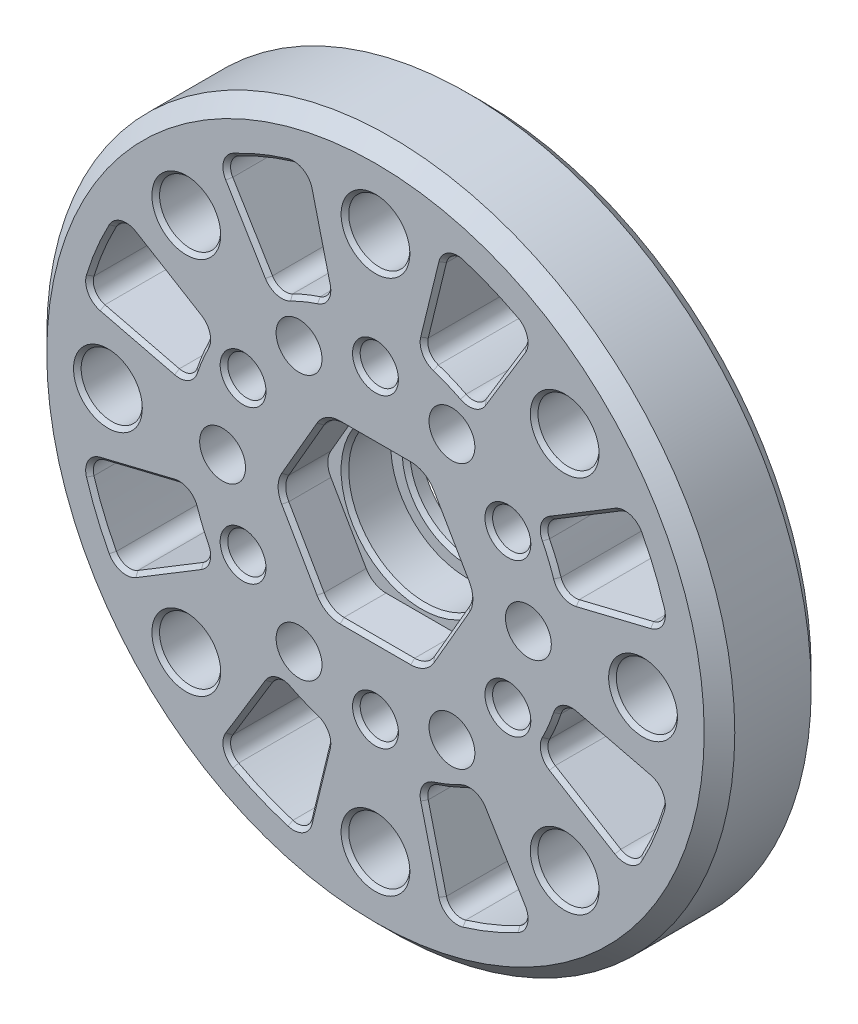
SolidWorks part; units mm, degrees
material "A2017"
ref_plane "正面" through (0, 0, 0) normal (0, 0, 1) x (1, 0, 0)
ref_plane "平面" through (0, 0, 0) normal (0, 1, 0) x (1, 0, 0)
ref_plane "右側面" through (0, 0, 0) normal (1, 0, 0) x (0, 0, -1)
sketch "ｽｹｯﾁ1" plane through (0, 0, 0) normal (0, 0, 1) x (1, 0, 0)
  circle A0 centre (0, 0) radius 17.5 construction
  circle A1 centre (0, 17.5) radius 2
  circle A2 centre (12.3744, 12.3744) radius 2
  circle A3 centre (17.5, 0) radius 2
  circle A4 centre (12.3744, -12.3744) radius 2
  circle A5 centre (0, -17.5) radius 2
  circle A6 centre (-12.3744, -12.3744) radius 2
  circle A7 centre (-17.5, 0) radius 2
  circle A8 centre (-12.3744, 12.3744) radius 2
  circle A9 centre (0, 0) radius 22.5
  point P21 (0, 0)
  dimension "D1" = 35
  dimension "D2" = 4
  dimension "D4" = 45
  dimension "D3" = 8
extrude "ﾎﾞｽ - 押し出し1" add sketch "ｽｹｯﾁ1" along normal blind 7
sketch "ｽｹｯﾁ2" plane through (0, 0, 7) normal (0, 0, 1) x (1, 0, 0)
  circle A0 centre (0, 7.1696) radius 1.0285
extrude "ﾎﾞｽ - 押し出し2" [suppressed] add sketch "ｽｹｯﾁ2" along normal blind 10
sketch "ｽｹｯﾁ3" plane through (0, 0, 7) normal (0, 0, 1) x (1, 0, 0)
  circle A0 centre (2, 0) radius 3
  dimension "D1" = 6
  dimension "D2" = 2
extrude "ｶｯﾄ - 押し出し1" [suppressed] cut sketch "ｽｹｯﾁ3" against normal through all
sketch "ｽｹｯﾁ5" plane through (0, 0, 7) normal (0, 0, 1) x (1, 0, 0)
  line L0 (0, 0) -> (0, 22) construction
  line L1 (0, 0) -> (7.5244, 20.6732) construction
  arc A1 (-7.5244, 20.6732) -> (7.5244, 20.6732) centre (0, 0) cw construction
  arc A2 (7.952, 21.8479) -> (-7.952, 21.8479) centre (0, 0) ccw
  arc A3 (7.0969, 19.4986) -> (-7.0969, 19.4986) centre (0, 0) ccw
  arc A4 (7.0969, 19.4986) -> (7.952, 21.8479) centre (7.5244, 20.6732) ccw
  arc A5 (-7.952, 21.8479) -> (-7.0969, 19.4986) centre (-7.5244, 20.6732) ccw
  arc A6 (14.1413, 16.853) -> (21.6658, 3.8203) centre (0, 0) cw construction
  arc A7 (22.8968, 4.0373) -> (14.9448, 17.8105) centre (0, 0) ccw
  arc A8 (20.4348, 3.6032) -> (13.3378, 15.8954) centre (0, 0) ccw
  arc A9 (20.4348, 3.6032) -> (22.8968, 4.0373) centre (21.6658, 3.8203) ccw
  arc A10 (14.9448, 17.8105) -> (13.3378, 15.8954) centre (14.1413, 16.853) ccw
  arc A11 (21.6658, -3.8203) -> (14.1413, -16.853) centre (0, 0) cw construction
  arc A12 (14.9448, -17.8105) -> (22.8968, -4.0373) centre (0, 0) ccw
  arc A13 (13.3378, -15.8954) -> (20.4348, -3.6032) centre (0, 0) ccw
  arc A14 (13.3378, -15.8954) -> (14.9448, -17.8105) centre (14.1413, -16.853) ccw
  arc A15 (22.8968, -4.0373) -> (20.4348, -3.6032) centre (21.6658, -3.8203) ccw
  arc A16 (7.5244, -20.6732) -> (-7.5244, -20.6732) centre (0, 0) cw construction
  arc A17 (-7.952, -21.8479) -> (7.952, -21.8479) centre (0, 0) ccw
  arc A18 (-7.0969, -19.4986) -> (7.0969, -19.4986) centre (0, 0) ccw
  arc A19 (-7.0969, -19.4986) -> (-7.952, -21.8479) centre (-7.5244, -20.6732) ccw
  arc A20 (7.952, -21.8479) -> (7.0969, -19.4986) centre (7.5244, -20.6732) ccw
  arc A21 (-14.1413, -16.853) -> (-21.6658, -3.8203) centre (0, 0) cw construction
  arc A22 (-22.8968, -4.0373) -> (-14.9448, -17.8105) centre (0, 0) ccw
  arc A23 (-20.4348, -3.6032) -> (-13.3378, -15.8954) centre (0, 0) ccw
  arc A24 (-20.4348, -3.6032) -> (-22.8968, -4.0373) centre (-21.6658, -3.8203) ccw
  arc A25 (-14.9448, -17.8105) -> (-13.3378, -15.8954) centre (-14.1413, -16.853) ccw
  arc A26 (-21.6658, 3.8203) -> (-14.1413, 16.853) centre (0, 0) cw construction
  arc A27 (-14.9448, 17.8105) -> (-22.8968, 4.0373) centre (0, 0) ccw
  arc A28 (-13.3378, 15.8954) -> (-20.4348, 3.6032) centre (0, 0) ccw
  arc A29 (-13.3378, 15.8954) -> (-14.9448, 17.8105) centre (-14.1413, 16.853) ccw
  arc A30 (-22.8968, 4.0373) -> (-20.4348, 3.6032) centre (-21.6658, 3.8203) ccw
  circle A31 centre (0, 0) radius 22 construction
  point P7 (0, 22)
  point P19 (19.0526, 11)
  point P26 (19.0526, -11)
  point P33 (0, -22)
  point P40 (-19.0526, -11)
  point P47 (-19.0526, 11)
  point P52 (0, 0)
  dimension "D1" = 1.25
  dimension "D3" = 20
  dimension "D2" = 44
  dimension "D4" = 6
extrude "ｶｯﾄ - 押し出し2" [suppressed] cut sketch "ｽｹｯﾁ5" against normal through all
sketch "ｽｹｯﾁ7" plane through (0, 0, 7) normal (0, 0, 1) x (1, 0, 0)
  circle A0 centre (0, 0) radius 5
  circle A1 centre (0, 0) radius 10 construction
  circle A2 centre (0, 10) radius 5 construction
  circle A3 centre (0, 10) radius 0.5
  circle A4 centre (8.6603, 5) radius 5 construction
  circle A5 centre (8.6603, 5) radius 0.5
  circle A6 centre (8.6603, -5) radius 5 construction
  circle A7 centre (8.6603, -5) radius 0.5
  circle A8 centre (0, -10) radius 5 construction
  circle A9 centre (0, -10) radius 0.5
  circle A10 centre (-8.6603, -5) radius 5 construction
  circle A11 centre (-8.6603, -5) radius 0.5
  circle A12 centre (-8.6603, 5) radius 5 construction
  circle A13 centre (-8.6603, 5) radius 0.5
  point P24 (0, 0)
  dimension "D1" = 10
  dimension "D2" = 20
  dimension "D3" = 1
  dimension "D4" = 6
extrude "ｶｯﾄ - 押し出し3" cut sketch "ｽｹｯﾁ7" against normal through all
hole_wizard "M3x0.5 ねじ穴1" positions "ｽｹｯﾁ8" profile "ｽｹｯﾁ9" tap size "M3x0.5" standard "JIS" end condition through all
sketch "ｽｹｯﾁ8" plane through (0, 0, 7) normal (0, 0, 1) x (1, 0, 0)
  point P0 (0, 10)
  point P3 (8.6603, 5)
  point P6 (8.6603, -5)
  point P9 (0, -10)
  point P12 (-8.6603, -5)
  point P15 (-8.6603, 5)
cosmetic thread "穴のねじ山7" parameters "D2"=3
cosmetic thread "穴のねじ山8" parameters "D2"=3
cosmetic thread "穴のねじ山9" parameters "D2"=3
cosmetic thread "穴のねじ山10" parameters "D2"=3
cosmetic thread "穴のねじ山11" parameters "D2"=3
cosmetic thread "穴のねじ山12" parameters "D2"=3
sketch "ｽｹｯﾁ9" plane through (0, 10, 7) normal (1, 0, 0) x (0, -1, 0)
  line L0 (0, 0) -> (0, 7)
  line L1 (0, 7) -> (1.25, 7)
  line L2 (1.25, 7) -> (1.25, 0.25)
  line L3 (1.25, 0.25) -> (1.5, 0)
  line L5 (1.5, 0) -> (0, 0)
  line L6 (-1.25, 0.25) -> (-1.5, 0) construction
  line L11 (0, -6.35) -> (0, 107.95) construction
  dimension "次ｻｰﾌｪｽまでのねじ下穴ﾄﾞﾘﾙ直径" = 2.5
  dimension "次ｻｰﾌｪｽまでのねじ下穴ﾄﾞﾘﾙの深さ" = 7
  dimension "表面の皿穴の直径" = 3
  dimension "表面の皿穴の角度" = 90
chamfer "面取り1" distance 1 angle 45 2 edges at (22.5, 0, 0) (22.5, 0, 7)
sketch "ｽｹｯﾁ10" plane through (0, 0, 7) normal (0, 0, 1) x (1, 0, 0)
  line L0 (6.697, 16.1679) -> (0, 0) construction
  line L1 (6.4847, 10.6864) -> (10.1161, 16.6708)
  line L2 (2.9711, 12.1418) -> (4.6349, 18.9412)
  line L3 (0, 0) -> (2.9711, 12.1418) construction
  circle A0 centre (0, 0) radius 19.5 construction
  circle A2 centre (0, 0) radius 12.5 construction
  arc A3 (0, 17.5) -> (12.3744, 12.3744) centre (0, 0) cw construction
  circle A4 centre (0, 17.5) radius 2 construction
  arc A5 (2.9711, 12.1418) -> (6.4847, 10.6864) centre (0, 0) cw
  arc A6 (4.6349, 18.9412) -> (10.1161, 16.6708) centre (0, 0) cw
  dimension "D1" = 25
  dimension "D2" = 17.5
extrude "ｶｯﾄ - 押し出し4" cut sketch "ｽｹｯﾁ10" against normal through all
fillet "ﾌｨﾚｯﾄ1" radius 1 4 edges at (6.4847, 10.6864, 3.5) (2.9711, 12.1418, 3.5) (10.1161, 16.6708, 3.5) (4.6349, 18.9412, 3.5)
pattern_circular "円形ﾊﾟﾀｰﾝ1" count 8 over 360 about axis through (0, 0, 0) along (0, 0, 1) of "ｶｯﾄ - 押し出し4", "ﾌｨﾚｯﾄ1"
sketch "ｽｹｯﾁ11" plane through (0, 0, 7) normal (0, 0, 1) x (1, 0, 0)
  circle A0 centre (0, 0) radius 10.5 construction
  text T0 "<b>           1:15         cycloid gear system</b>" font "Century Gothic" height in points 10
  dimension "D1" = 21
chamfer "面取り2" [suppressed] distance 0.25 angle 45
extrude "ｶｯﾄ - 押し出し5" [suppressed] cut sketch "ｽｹｯﾁ11" against normal blind 0.05
sketch "ｽｹｯﾁ12" plane through (0, 0, 0) normal (0, 0, 1) x (1, 0, 0)
  circle A0 centre (0, 0) radius 5 construction
  circle A1 centre (0, 0) radius 5
  circle A2 centre (0, 0) radius 4
  dimension "D1" = 8
extrude "ﾎﾞｽ - 押し出し3" add sketch "ｽｹｯﾁ12" along normal blind 1
chamfer "面取り3" distance 0.25 angle 45 9 edges at (4, 0, 1) (2, 17.5, 7) (14.3744, 12.3744, 7) (19.5, 0, 7) (14.3744, -12.3744, 7) (2, -17.5, 7) (-10.3744, -12.3744, 7) (-15.5, 0, 7) (-10.3744, 12.3744, 7)
fillet "ﾌｨﾚｯﾄ3" [suppressed] radius 0.5
sketch "ｽｹｯﾁ14" plane through (0, 0, 7) normal (0, 0, 1) x (1, 0, 0)
  line L1 (3.1754, 5.5) -> (-3.1754, 5.5)
  line L2 (-3.1754, 5.5) -> (-6.3509, 0)
  line L3 (-6.3509, 0) -> (-3.1754, -5.5)
  line L4 (-3.1754, -5.5) -> (3.1754, -5.5)
  line L5 (3.1754, -5.5) -> (6.3509, 0)
  line L6 (6.3509, 0) -> (3.1754, 5.5)
  circle A0 centre (0, 0) radius 5.5 construction
  dimension "D1" = 11
extrude "ｶｯﾄ - 押し出し6" cut sketch "ｽｹｯﾁ14" against normal blind 3
fillet "ﾌｨﾚｯﾄ4" radius 1.5 6 edges at (3.1754, -5.5, 5.5) (6.3509, 0, 5.5) (3.1754, 5.5, 5.5) (-6.3509, 0, 5.5) (-3.1754, -5.5, 5.5) (-3.1754, 5.5, 5.5)
chamfer "面取り5" distance 0.25 angle 45 13 edges at (5, 0, 4) (6.1188, 0, 7) (4.7631, -2.75, 7) (4.7631, 2.75, 7) (3.0594, -5.299, 7) (3.0594, 5.299, 7) (0, -5.5, 7) (0, 5.5, 7) (-3.0594, -5.299, 7) (-3.0594, 5.299, 7) (-4.7631, -2.75, 7) (-4.7631, 2.75, 7) (-6.1188, 0, 7)
sketch "ｽｹｯﾁ15" plane through (0, 0, 0) normal (0, 0, -1) x (-1, 0, 0)
  circle A0 centre (0, 0) radius 26.5
  circle A1 centre (0, 0) radius 22.5 construction
  dimension "D1" = 4
chamfer "面取り6" [suppressed] distance 0.2 angle 45
chamfer "面取り7" [suppressed] distance 0.25 angle 45
chamfer "面取り8" distance 0.25 angle 45 64 edges at (-18.0157, -7.4623, 7) (-16.5754, -9.6929, 7) (-18.5745, -4.8666, 7) (-13.6512, -8.2837, 7) (-15.5103, -3.7954, 7) (-11.0665, -6.4028, 7) (-12.3527, -3.2977, 7) (-11.5485, -4.7835, 7) (-7.4623, -18.0157, 7) (-4.8666, -18.5745, 7) (-9.6929, -16.5754, 7) (-3.7954, -15.5103, 7) (-8.2837, -13.6512, 7) (-3.2977, -12.3527, 7) (-6.4028, -11.0665, 7) (-4.7835, -11.5485, 7) (7.4623, -18.0157, 7) (9.6929, -16.5754, 7) (4.8666, -18.5745, 7) (8.2837, -13.6512, 7) (3.7954, -15.5103, 7) (6.4028, -11.0665, 7) (3.2977, -12.3527, 7) (4.7835, -11.5485, 7) (15.5103, 3.7954, 7) (18.5745, 4.8666, 7) (12.3527, 3.2977, 7) (18.0157, 7.4623, 7) (11.5485, 4.7835, 7) (16.5754, 9.6929, 7) (11.0665, 6.4028, 7) (13.6512, 8.2837, 7) (4.7835, 11.5485, 7) (6.4028, 11.0665, 7) (3.2977, 12.3527, 7) (8.2837, 13.6512, 7) (3.7954, 15.5103, 7) (9.6929, 16.5754, 7) (4.8666, 18.5745, 7) (7.4623, 18.0157, 7) (-4.7835, 11.5485, 7) (-3.2977, 12.3527, 7) (-6.4028, 11.0665, 7) (-3.7954, 15.5103, 7) (-8.2837, 13.6512, 7) (-4.8666, 18.5745, 7) (-9.6929, 16.5754, 7) (-7.4623, 18.0157, 7) (-15.5103, 3.7954, 7) (-12.3527, 3.2977, 7) (-18.5745, 4.8666, 7) (-11.5485, 4.7835, 7) (-18.0157, 7.4623, 7) (-11.0665, 6.4028, 7) (-16.5754, 9.6929, 7) (-13.6512, 8.2837, 7) (15.5103, -3.7954, 7) (12.3527, -3.2977, 7) (18.5745, -4.8666, 7) (11.5485, -4.7835, 7) (18.0157, -7.4623, 7) (11.0665, -6.4028, 7) (16.5754, -9.6929, 7) (13.6512, -8.2837, 7)
sketch "ｽｹｯﾁ16" [suppressed] plane through (0, 0, 7) normal (0, 0, 1) x (1, 0, 0)
  circle A2 centre (0, 0) radius 26.5
  circle A3 centre (0, 0) radius 26.5
  dimension "D1" = 4
sketch "ｽｹｯﾁ18" plane through (0, 0, 7) normal (0, 0, 1) x (1, 0, 0)
  line L0 (0, 10) -> (0, 0) construction
  line L1 (0, 0) -> (5, 8.6603) construction
  circle A0 centre (0, 0) radius 10 construction
  circle A1 centre (5, 8.6603) radius 1.5
  circle A2 centre (10, 0) radius 1.5
  circle A3 centre (5, -8.6603) radius 1.5
  circle A4 centre (-5, -8.6603) radius 1.5
  circle A5 centre (-10, 0) radius 1.5
  circle A6 centre (-5, 8.6603) radius 1.5
  point P19 (0, 0)
  dimension "D2" = 3
  dimension "D1" = 30
  dimension "D3" = 6
extrude "ｶｯﾄ - 押し出し7" cut sketch "ｽｹｯﾁ18" against normal through all
